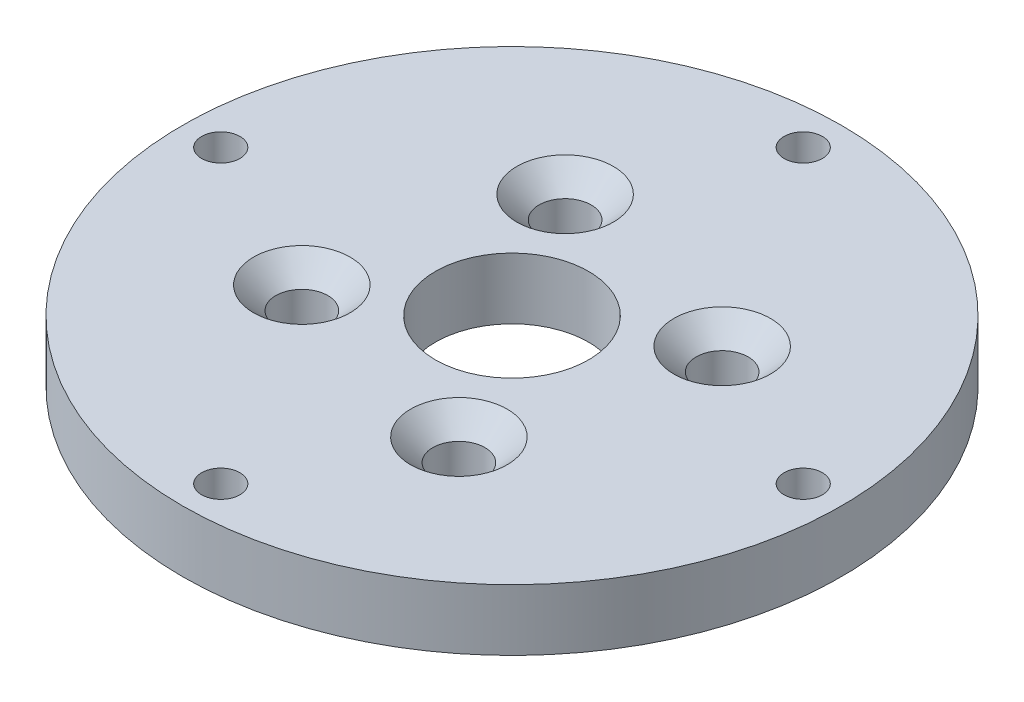
SolidWorks part; units mm, degrees
ref_plane "Plan de face" through (0, 0, 0) normal (0, 0, 1) x (1, 0, 0)
ref_plane "Plan de dessus" through (0, 0, 0) normal (0, 1, 0) x (1, 0, 0)
ref_plane "Plan de droite" through (0, 0, 0) normal (1, 0, 0) x (0, 0, -1)
sketch "Esquisse1" plane through (0, 0, 0) normal (0, 1, 0) x (1, 0, 0)
  circle A0 centre (0, 0) radius 21.5
  circle A1 centre (0, 0) radius 10 construction
  circle A2 centre (0, 0) radius 5
  circle A3 centre (-5.1233, 8.5879) radius 1
  circle A4 centre (8.5879, 5.1233) radius 1
  circle A5 centre (5.1233, -8.5879) radius 1
  circle A6 centre (-8.5879, -5.1233) radius 1
  circle A7 centre (0, 0) radius 16 construction
  circle A8 centre (0, 0) radius 19 construction
  circle A9 centre (0, 19) radius 1.25
  circle A10 centre (19, 0) radius 1.25
  circle A11 centre (0, -19) radius 1.25
  circle A12 centre (-19, 0) radius 1.25
  point P16 (0, 0)
  point P27 (0, 0)
  dimension "D1" = 2
  dimension "D3" = 43
  dimension "D4" = 20
  dimension "D5" = 10
  dimension "D6" = 32
  dimension "D8" = 2.5
  dimension "D9" = 38
  dimension "D2" = 4
  dimension "D7" = 4
extrude "Boss.-Extru.1" add sketch "Esquisse1" along normal blind 4
hole_wizard "Fraisage pour vis à tête fraisée M31" positions "Esquisse6" profile "Esquisse7" countersink size "M3" standard "Ansi Metric" end condition through all
sketch "Esquisse6" plane through (0, 4, 0) normal (0, 1, 0) x (1, 0, 0)
  point P0 (-5.1233, 8.5879)
  point P3 (8.5879, 5.1233)
  point P6 (5.1233, -8.5879)
  point P9 (-8.5879, -5.1233)
sketch "Esquisse7" plane through (-5.1233, 4, -8.5879) normal (1, 0, 0) x (0, 0, 1)
  line L0 (0, 0) -> (0, 4)
  line L1 (0, 4) -> (1.7, 4)
  line L2 (1.7, 4) -> (1.7, 1.45)
  line L3 (1.7, 1.45) -> (3.15, 0)
  line L5 (3.15, 0) -> (0, 0)
  line L6 (-1.7, 1.45) -> (-3.15, 0) construction
  line L11 (0, -6.35) -> (0, 107.95) construction
  dimension "Diamètre du perçage jusqu'au prochain" = 3.4
  dimension "Profondeur du perçage jusqu'au prochain" = 4
  dimension "Diamètre du fraisage entrant" = 6.3
  dimension "Angle du fraisage entrant" = 90
